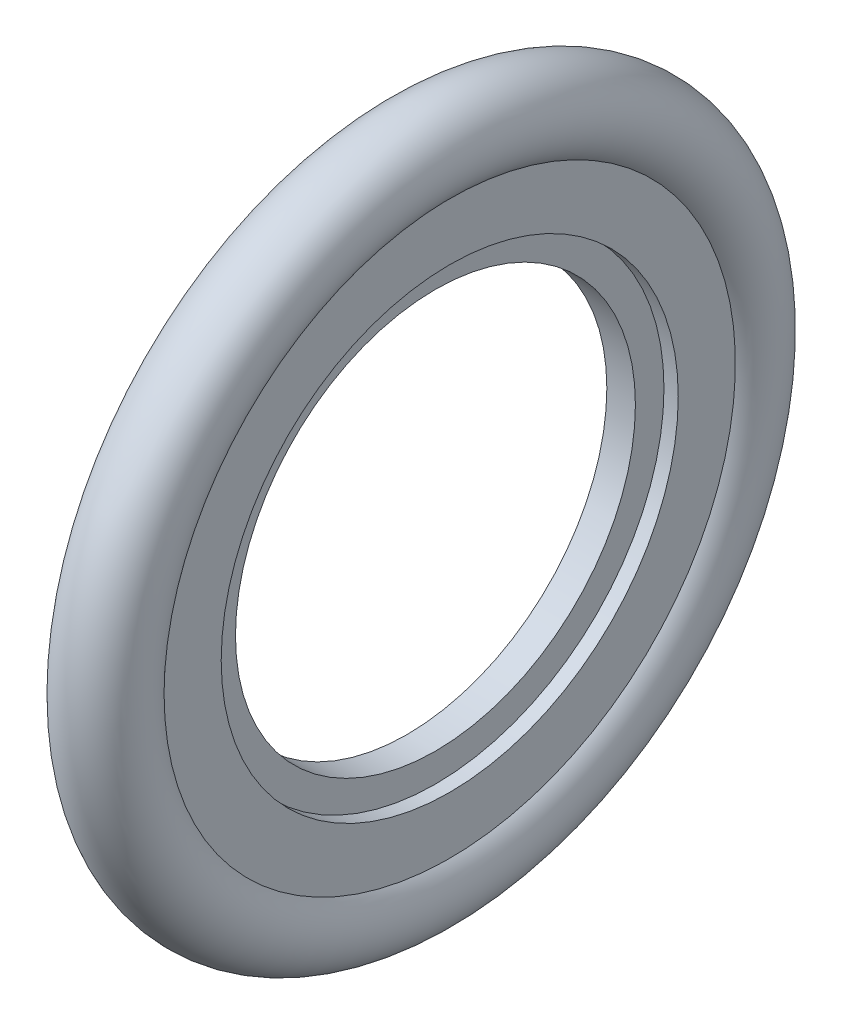
SolidWorks part; units mm, degrees
material "Polyurethane Foam Flexible"
ref_plane "Front" through (0, 0, 0) normal (0, 0, 1) x (1, 0, 0)
ref_plane "Top" through (0, 0, 0) normal (0, 1, 0) x (1, 0, 0)
ref_plane "Right" through (0, 0, 0) normal (1, 0, 0) x (0, 0, -1)
sketch "Sketch1" plane through (0, 0, 0) normal (0, 0, 1) x (1, 0, 0)
  line L0 (0, 0) -> (0, 44.45) construction
  line L1 (3.175, 44.45) -> (-3.175, 44.45)
  line L2 (-3.175, 44.45) -> (-3.175, 50.8)
  line L3 (-3.175, 50.8) -> (-6.35, 50.8)
  line L4 (-6.35, 50.8) -> (-6.35, 63.5)
  line L5 (3.175, 44.45) -> (3.175, 50.8)
  line L6 (3.175, 50.8) -> (6.35, 50.8)
  line L7 (6.35, 50.8) -> (6.35, 63.5)
  line L8 (0, 0) -> (25.4, 0)
  arc A1 (-6.35, 63.5) -> (6.35, 63.5) centre (0, 70.1675) cw
  point P5 (0, 44.45)
  point P13 (0, 79.375)
  dimension "D1" = 44.45
  dimension "D2" = 6.35
  dimension "D3" = 12.7
  dimension "D4" = 6.35
  dimension "D5" = 12.7
  dimension "D6" = 12.7
  dimension "D7" = 15.875
  dimension "D8" = 25.4
revolve "Revolve1" add sketch "Sketch1" angle 360 about L8
